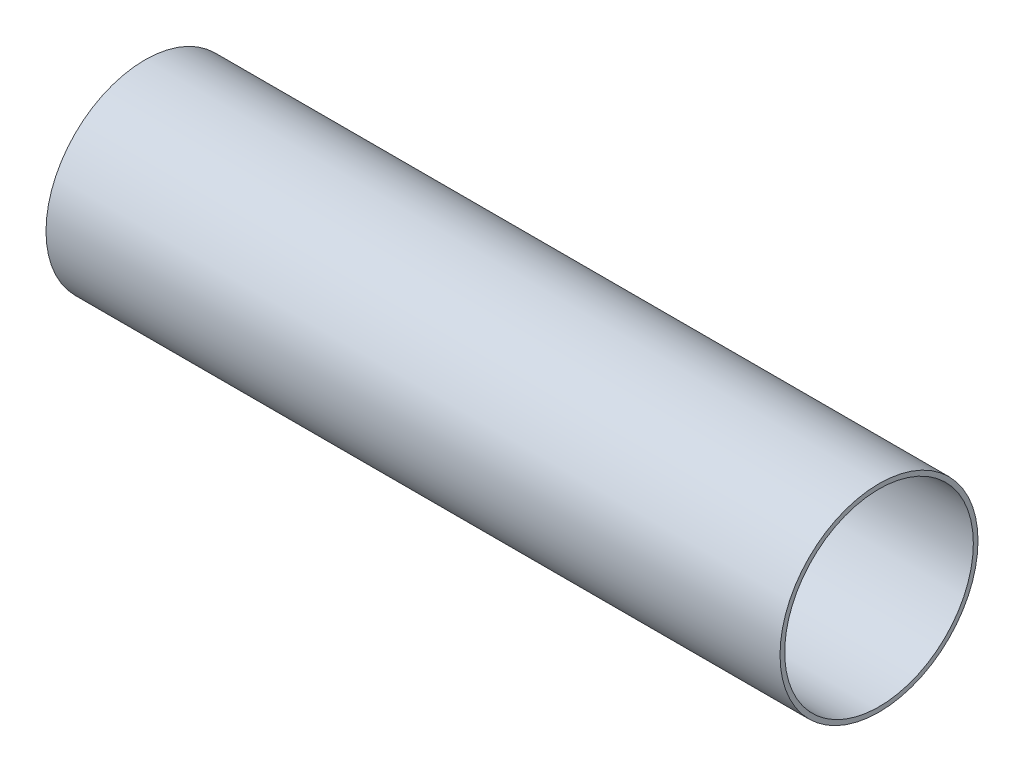
SolidWorks part; units mm, degrees
material "Thornel Mat VMA"
ref_plane "Front Plane" through (0, 0, 0) normal (0, 0, 1) x (1, 0, 0)
ref_plane "Top Plane" through (0, 0, 0) normal (0, 1, 0) x (1, 0, 0)
ref_plane "Right Plane" through (0, 0, 0) normal (1, 0, 0) x (0, 0, -1)
sketch "Sketch1" plane through (0, 0, 0) normal (1, 0, 0) x (0, 0, -1)
  circle A0 centre (0, 0) radius 16
  circle A1 centre (0, 0) radius 16.79
extrude "Boss-Extrude1" add sketch "Sketch1" along normal blind 124.5
